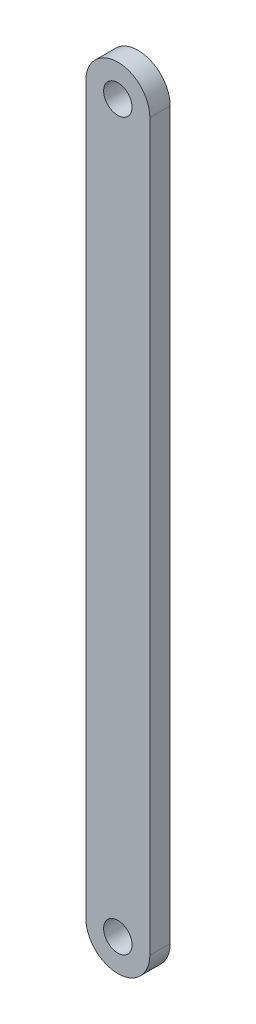
SolidWorks part; units mm, degrees
material "ABS"
ref_plane "Plano frontal" through (0, 0, 0) normal (0, 0, 1) x (1, 0, 0)
ref_plane "Plano superior" through (0, 0, 0) normal (0, 1, 0) x (1, 0, 0)
ref_plane "Plano direito" through (0, 0, 0) normal (1, 0, 0) x (0, 0, -1)
sketch "Esboço1" plane through (0, 0, 0) normal (0, 0, 1) x (1, 0, 0)
  line L0 (0, 0) -> (0, 170) construction
  line L1 (-7.5, 0) -> (-7.5, 170)
  line L2 (7.5, 0) -> (7.5, 170)
  arc A0 (-7.5, 0) -> (7.5, 0) centre (0, 0) ccw
  arc A1 (7.5, 170) -> (-7.5, 170) centre (0, 170) ccw
  circle A5 centre (0, 170) radius 3.325
  circle A6 centre (0, 0) radius 3.325
  point P3 (0, 85)
  dimension "D1" = 6.65
  dimension "D3" = 6.65
  dimension "D4" = 170
  dimension "D5" = 15
extrude "Ressalto-extrusão1" add sketch "Esboço1" along normal blind 4.7625
